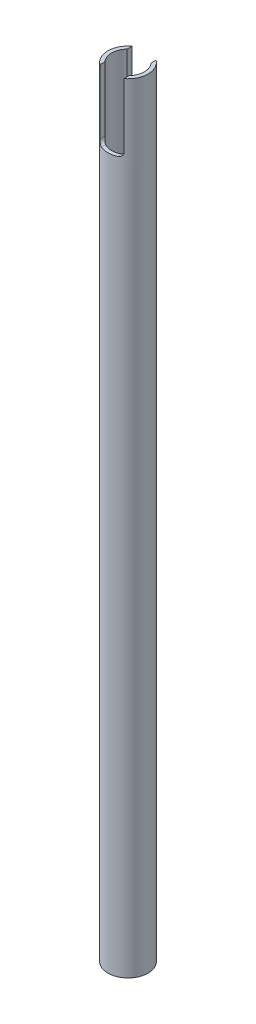
SolidWorks part; units mm, degrees
material "AISI 4130 Steel, normalized at 870C"
ref_plane "X-Y Datum" through (0, 0, 0) normal (0, 0, 1) x (1, 0, 0)
ref_plane "X-Z Datum" through (0, 0, 0) normal (0, 1, 0) x (1, 0, 0)
ref_plane "Y-Z Datum" through (0, 0, 0) normal (1, 0, 0) x (0, 0, -1)
sketch "Sketch1" plane through (0, 0, 0) normal (0, 1, 0) x (1, 0, 0)
  circle A0 centre (0, 0) radius 7.9375
  circle A1 centre (0, 0) radius 6.4643
  dimension "D1" = 1.4732
  dimension "D2" = 15.875
extrude "Boss-Extrude1" add sketch "Sketch1" along normal offset from surface (307.9909 mm away) 25.4 from surface at -148.1614
sketch "Sketch2" plane through (0, 0, 0) normal (0, 0, 1) x (1, 0, 0)
  line L0 (0, 159.8295) -> (0, 132.842) construction
  line L1 (4.7625, 159.8295) -> (-4.7625, 159.8295)
  line L2 (4.7625, 159.8295) -> (4.7625, 134.4295)
  line L3 (3.175, 132.842) -> (-3.175, 132.842)
  line L4 (-4.7625, 159.8295) -> (-4.7625, 134.4295)
  line L8 (4.7625, 137.6045) -> (4.7625, 170.1302) construction
  line L9 (-4.7625, 134.4295) -> (4.7625, 134.4295) construction
  arc A2 (4.7625, 134.4295) -> (3.175, 132.842) centre (3.175, 134.4295) cw
  arc A3 (-4.7625, 134.4295) -> (-3.175, 132.842) centre (-3.175, 134.4295) ccw
  dimension "D1" = 1.5875
  dimension "D2" = 1.5875
  dimension "D3" = 26.9875
extrude "Cut-Extrude1" cut sketch "Sketch2" against normal through all both and the other way through all
